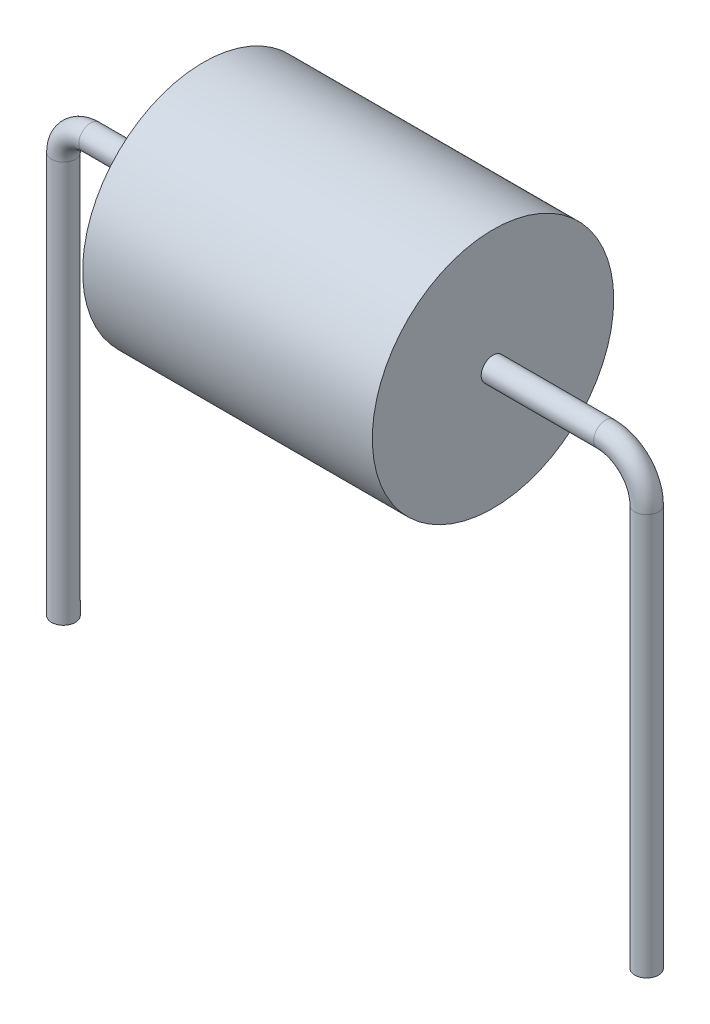
SolidWorks part; units mm, degrees
ref_plane "Ön Düzlem" through (0, 0, 0) normal (0, 0, 1) x (1, 0, 0)
ref_plane "Üst Düzlem" through (0, 0, 0) normal (0, 1, 0) x (1, 0, 0)
ref_plane "Sağ Düzlem" through (0, 0, 0) normal (1, 0, 0) x (0, 0, -1)
sketch "Çizim1" plane through (0, 0, 0) normal (1, 0, 0) x (0, 0, -1)
  circle A0 centre (0, 0) radius 2.5
  dimension "D1" = 5
extrude "Yükseklik-Ekstrüzyon1" add sketch "Çizim1" along normal blind 6
sketch "Çizim4" plane through (0, 0, 0) normal (0, 0, 1) x (1, 0, 0)
  line L0 (0, 0) -> (-2.3326, 0)
  line L1 (-2.8982, -0.5656) -> (-2.8982, -8.8726)
  arc A0 (-2.3326, 0) -> (-2.8982, -0.5656) centre (-2.3326, -0.5656) ccw
ref_plane "Düzlem1" through (-2.8982, -8.8726, 0) normal (0, -1, 0) x (-1, 0, 0)
sketch "Çizim5" plane through (-2.8982, -8.8726, 0) normal (0, -1, 0) x (-1, 0, 0)
  circle A0 centre (-0.001, 0) radius 0.2465
sweep "Süpür1" add profiles "Çizim5" path "Çizim4"
sketch "Çizim6" plane through (0, 0, 0) normal (0, 0, 1) x (1, 0, 0)
  line L0 (6, 0) -> (8.33, 0)
  line L1 (6, -2.5) -> (6, 2.5) construction
  line L2 (9.18, -0.85) -> (9.18, -9.16)
  arc A0 (8.33, 0) -> (9.18, -0.85) centre (8.33, -0.85) cw
  dimension "D2" = 0.85
  dimension "D1" = 2.33
  dimension "D3" = 8.31
ref_plane "Düzlem2" through (9.18, -9.16, 0) normal (0, -1, 0) x (-1, 0, 0)
sketch "Çizim7" plane through (9.18, -9.16, 0) normal (0, -1, 0) x (-1, 0, 0)
  circle A0 centre (-0.0024, 0) radius 0.245
  dimension "D1" = 0.49
sweep "Süpür2" add profiles "Çizim7" path "Çizim6"
